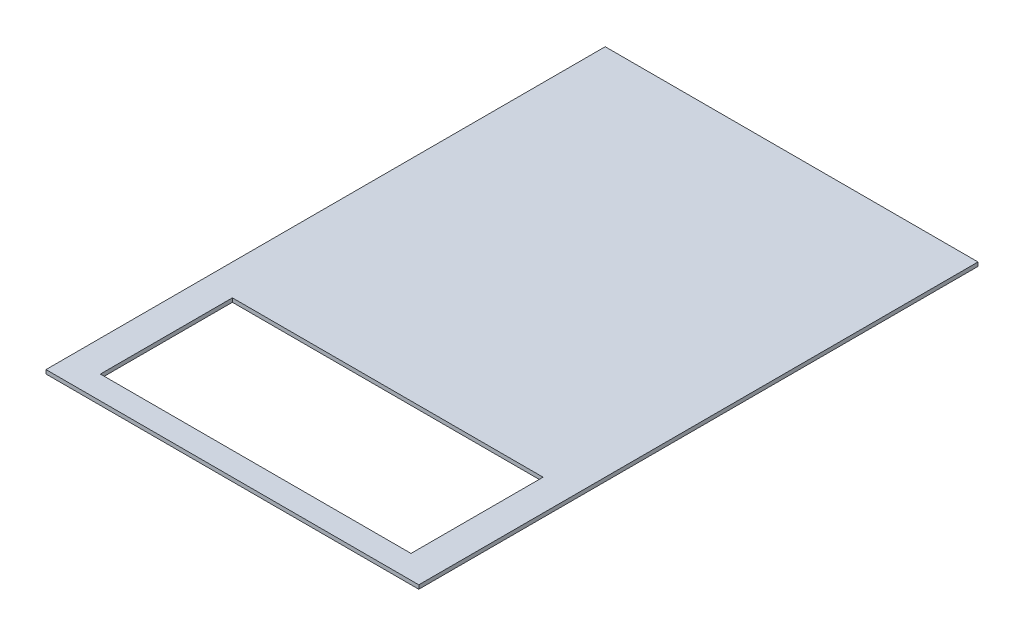
SolidWorks part; units mm, degrees
ref_plane "Front Plane" through (0, 0, 0) normal (0, 0, 1) x (1, 0, 0)
ref_plane "Top Plane" through (0, 0, 0) normal (0, 1, 0) x (1, 0, 0)
ref_plane "Right Plane" through (0, 0, 0) normal (1, 0, 0) x (0, 0, -1)
sketch "Sketch1" plane through (0, 0, 0) normal (0, 1, 0) x (1, 0, 0)
  line L1 (-304.8, -457.2) -> (304.8, -457.2)
  line L2 (-304.8, -457.2) -> (-304.8, 457.2)
  line L3 (-304.8, 457.2) -> (304.8, 457.2)
  line L4 (304.8, -457.2) -> (304.8, 457.2)
  line L5 (-304.8, -457.2) -> (304.8, 457.2) construction
  line L6 (-304.8, 457.2) -> (304.8, -457.2) construction
  point P0 (0, 0)
  dimension "D1" = 609.6
  dimension "D2" = 914.4
extrude "Boss-Extrude1" add sketch "Sketch1" along normal blind 6.35
sketch "Sketch2" plane through (0, 6.35, 0) normal (0, 1, 0) x (1, 0, 0)
  line L0 (0, 0) -> (0, -311.15) construction
  line L5 (304.8, -457.2) -> (304.8, 457.2) construction
  line L6 (-254, -419.1) -> (254, -419.1)
  line L7 (-254, -419.1) -> (-254, -203.2)
  line L8 (-254, -203.2) -> (254, -203.2)
  line L17 (254, -419.1) -> (254, -203.2)
  line L18 (-254, -419.1) -> (254, -203.2) construction
  line L19 (-254, -203.2) -> (254, -419.1) construction
  dimension "D1" = 215.9
  dimension "D2" = 50.8
  dimension "D3" = 203.2
extrude "Cut-Extrude1" cut sketch "Sketch2" against normal through all
